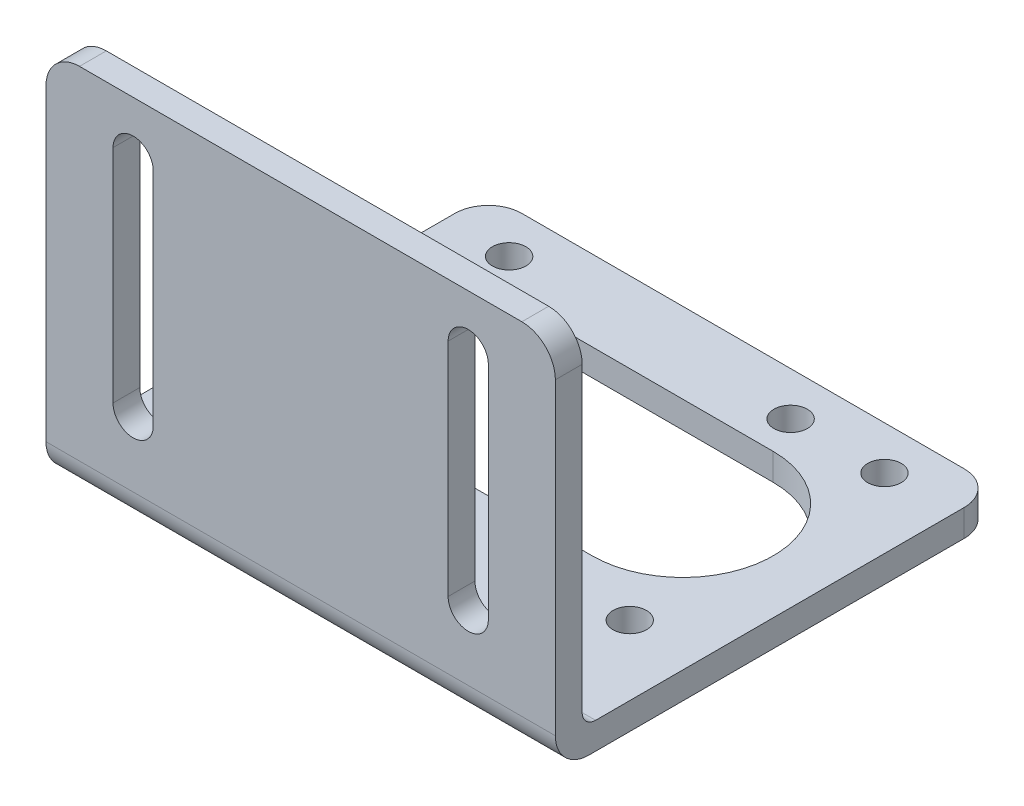
SolidWorks part; units mm, degrees
ref_plane "Front Plane" through (0, 0, 0) normal (0, 0, 1) x (1, 0, 0)
ref_plane "Top Plane" through (0, 0, 0) normal (0, 1, 0) x (1, 0, 0)
ref_plane "Right Plane" through (0, 0, 0) normal (1, 0, 0) x (0, 0, -1)
sketch "Sketch1" plane through (0, 0, 0) normal (1, 0, 0) x (0, 0, -1)
  line L1 (0, 0) -> (66, 0)
  line L2 (0, 0) -> (0, 4)
  line L3 (0, 4) -> (66, 4)
  line L4 (66, 0) -> (66, 4)
  line L5 (0, 0) -> (4, 0)
  line L6 (0, 0) -> (0, 56)
  line L7 (0, 56) -> (4, 56)
  line L8 (4, 0) -> (4, 56)
  dimension "D1" = 4
  dimension "D2" = 56
  dimension "D3" = 66
extrude "Boss-Extrude1" add sketch "Sketch1" along normal blind 76 contours L3 L8 L7 L6 | L1 L8 L3 L2 | L8 L1 L4 L3
sketch "Sketch2" plane through (0, 0, 0) normal (0, -1, 0) x (1, 0, 0)
  line L0 (38, 0) -> (38, -66) construction
  line L1 (76, 0) -> (0, 0) construction
  line L2 (76, -66) -> (0, -66) construction
  line L3 (54.5, -40.5) -> (21.5, -40.5) construction
  line L4 (54.5, -54) -> (21.5, -54)
  line L5 (54.5, -27) -> (21.5, -27)
  line L6 (68, -66) -> (68, 0) construction
  line L7 (76, -59.5) -> (0, -59.5) construction
  line L8 (8, -66) -> (8, 0) construction
  line L9 (76, 0) -> (76, -66) construction
  line L10 (0, 0) -> (0, -66) construction
  line L11 (76, -21.5) -> (0, -21.5) construction
  line L12 (9.6, -66) -> (9.6, 0) construction
  line L13 (65.6, 0) -> (65.6, -66) construction
  arc A0 (54.5, -54) -> (54.5, -27) centre (54.5, -40.5) ccw
  arc A1 (21.5, -27) -> (21.5, -54) centre (21.5, -40.5) ccw
  circle A2 centre (9.6, -59.5) radius 2.5
  circle A3 centre (9.6, -21.5) radius 2.5
  circle A4 centre (23.6, -21.5) radius 2.5
  circle A5 centre (65.6, -21.5) radius 2.5
  circle A6 centre (65.6, -59.5) radius 2.5
  circle A7 centre (51.6, -59.5) radius 2.5
  point P8 (38, -40.5)
  point P13 (38, -54)
  dimension "D4" = 9.6
  dimension "D5" = 38
  dimension "D6" = 5
  dimension "D8" = 14
  dimension "D9" = 42
  dimension "D10" = 14
  dimension "D1" = 27
  dimension "D2" = 60
  dimension "D3" = 6.5
  dimension "D7" = 19
extrude "Cut-Extrude1" cut sketch "Sketch2" against normal through all
sketch "Sketch3" plane through (0, 0, 0) normal (0, 0, 1) x (1, 0, 0)
  line L0 (38, 56) -> (38, 0) construction
  line L1 (76, 56) -> (0, 56) construction
  line L2 (76, 0) -> (0, 0) construction
  line L3 (13, 48) -> (13, 15) construction
  line L4 (16, 48) -> (16, 15)
  line L5 (10, 48) -> (10, 15)
  line L6 (0, 51) -> (76, 51) construction
  line L7 (0, 0) -> (0, 56) construction
  line L8 (76, 0) -> (76, 56) construction
  line L14 (0, 12) -> (76, 12) construction
  line L15 (63, 48) -> (63, 15) construction
  line L16 (60, 48) -> (60, 15)
  line L17 (66, 48) -> (66, 15)
  arc A0 (16, 48) -> (10, 48) centre (13, 48) ccw
  arc A1 (10, 15) -> (16, 15) centre (13, 15) ccw
  arc A2 (60, 48) -> (66, 48) centre (63, 48) cw
  arc A3 (66, 15) -> (60, 15) centre (63, 15) cw
  point P8 (13, 31.5)
  point P23 (63, 31.5)
  dimension "D1" = 5
  dimension "D2" = 10
  dimension "D3" = 6
  dimension "D4" = 39
extrude "Cut-Extrude2" cut sketch "Sketch3" against normal through all
fillet "Fillet1" radius 5 5 edges at (38, 0, 0) (0, 56, -2) (76, 56, -2) (0, 2, -66) (76, 2, -66)
fillet "Fillet2" radius 2 1 edges at (38, 4, -4)
